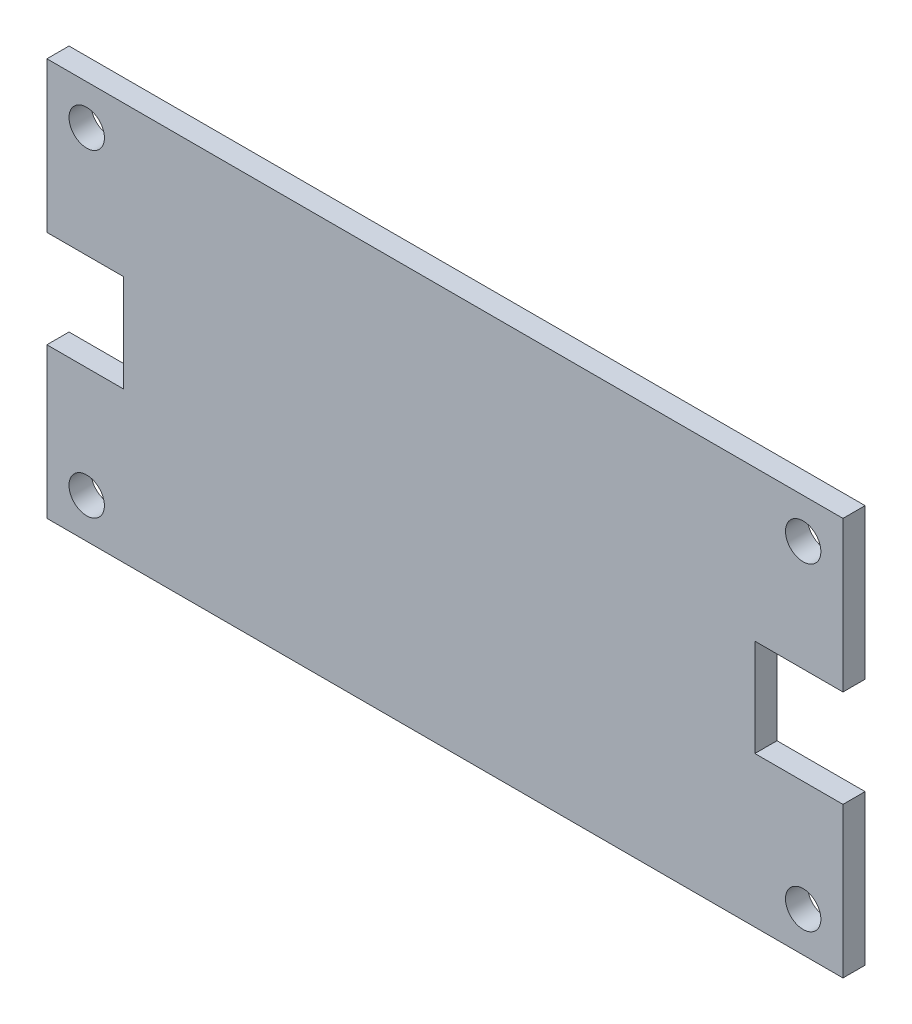
SolidWorks part; units mm, degrees
ref_plane "Front Plane" through (0, 0, 0) normal (0, 0, 1) x (1, 0, 0)
ref_plane "Top Plane" through (0, 0, 0) normal (0, 1, 0) x (1, 0, 0)
ref_plane "Right Plane" through (0, 0, 0) normal (1, 0, 0) x (0, 0, -1)
sketch "Sketch1" plane through (0, 0, 0) normal (0, 0, 1) x (1, 0, 0)
  line L1 (-90, 45) -> (90, 45)
  line L2 (-90, 45) -> (-90, -45)
  line L3 (-90, -45) -> (90, -45)
  line L4 (90, 45) -> (90, -45)
  line L5 (-90, 45) -> (90, -45) construction
  line L6 (-90, -45) -> (90, 45) construction
  point P0 (0, 0)
  dimension "D1" = 180
  dimension "D2" = 90
extrude "Boss-Extrude1" add sketch "Sketch1" along normal blind 5
sketch "Sketch5" plane through (0, 0, 0) normal (0, 0, -1) x (-1, 0, 0)
  line L0 (-90, -45) -> (-90, 45) construction
  line L1 (-90, 11) -> (-74.0824, 11)
  line L2 (-90, 11) -> (-90, -11)
  line L3 (-90, -11) -> (-74.0824, -11)
  line L4 (-74.0824, 11) -> (-74.0824, -11)
  line L5 (90, 11) -> (76.7353, 11)
  line L6 (90, 11) -> (90, -11)
  line L7 (90, -11) -> (76.7353, -11)
  line L8 (76.7353, 11) -> (76.7353, -11)
  line L9 (90, 45) -> (90, -45) construction
  line L10 (-90, 45) -> (90, 45) construction
  line L11 (90, -45) -> (-90, -45) construction
  line L12 (-90, 45) -> (90, 45) construction
  point P10 (-90, 0)
  point P19 (83.3677, 11)
  dimension "D1" = 0
  dimension "D2" = 0
  dimension "D3" = 34
  dimension "D4" = 34
  dimension "D5" = 34
  dimension "D6" = 34
extrude "Cut-Extrude3" cut sketch "Sketch5" against normal through all
sketch "Sketch7" plane through (0, 0, 0) normal (0, 0, -1) x (-1, 0, 0)
  line L1 (-74.0824, 11) -> (-70.0824, 11)
  line L2 (-74.0824, 11) -> (-74.0824, -11)
  line L3 (-74.0824, -11) -> (-70.0824, -11)
  line L4 (-70.0824, 11) -> (-70.0824, -11)
  line L5 (76.7353, 11) -> (72.7353, 11)
  line L6 (76.7353, 11) -> (76.7353, -11)
  line L7 (76.7353, -11) -> (72.7353, -11)
  line L8 (72.7353, 11) -> (72.7353, -11)
  dimension "D1" = 4
  dimension "D2" = 4
extrude "Cut-Extrude13" cut sketch "Sketch7" against normal through all
sketch "Sketch8" plane through (0, 0, 0) normal (0, 0, -1) x (-1, 0, 0)
  line L0 (-90, 11) -> (-90, 45) construction
  line L1 (-90, 45) -> (90, 45) construction
  line L2 (0, 28.4453) -> (0, -35.2251) construction
  line L3 (-38.1728, 0) -> (43.7734, 0) construction
  circle A0 centre (-81, 36) radius 4
  circle A1 centre (81, 36) radius 4
  circle A2 centre (81, -36) radius 4
  circle A3 centre (-81, -36) radius 4
  dimension "D1" = 8
  dimension "D2" = 9
  dimension "D3" = 9
extrude "Cut-Extrude14" cut sketch "Sketch8" against normal through all
sketch "Sketch9" plane through (0, 0, 0) normal (0, 0, -1) x (-1, 0, 0)
  line L0 (-90, 45) -> (90, 45) construction
  line L1 (-50, -40) -> (-5, -40)
  line L2 (-50, -40) -> (-50, 40)
  line L3 (-50, 40) -> (-5, 40)
  line L4 (-5, -40) -> (-5, 40)
  line L5 (-50, -40) -> (-5, 40) construction
  line L6 (-50, 40) -> (-5, -40) construction
  line L7 (-90, -45) -> (-90, -11) construction
  point P0 (-27.5, 0)
  dimension "D1" = 80
  dimension "D2" = 45
  dimension "D3" = 5
  dimension "D4" = 40
extrude "Cut-Extrude15" cut sketch "Sketch9" against normal blind 3
sketch "Sketch10" plane through (0, 0, 0) normal (0, 0, -1) x (-1, 0, 0)
  line L1 (51, -24) -> (5, -24)
  line L2 (51, -24) -> (51, 24)
  line L3 (51, 24) -> (5, 24)
  line L4 (5, -24) -> (5, 24)
  line L5 (51, -24) -> (5, 24) construction
  line L6 (51, 24) -> (5, -24) construction
  line L7 (-90, 45) -> (90, 45) construction
  point P0 (28, 0)
  dimension "D1" = 48
  dimension "D2" = 46
  dimension "D3" = 5
  dimension "D4" = 21
extrude "Cut-Extrude16" cut sketch "Sketch10" against normal blind 3
